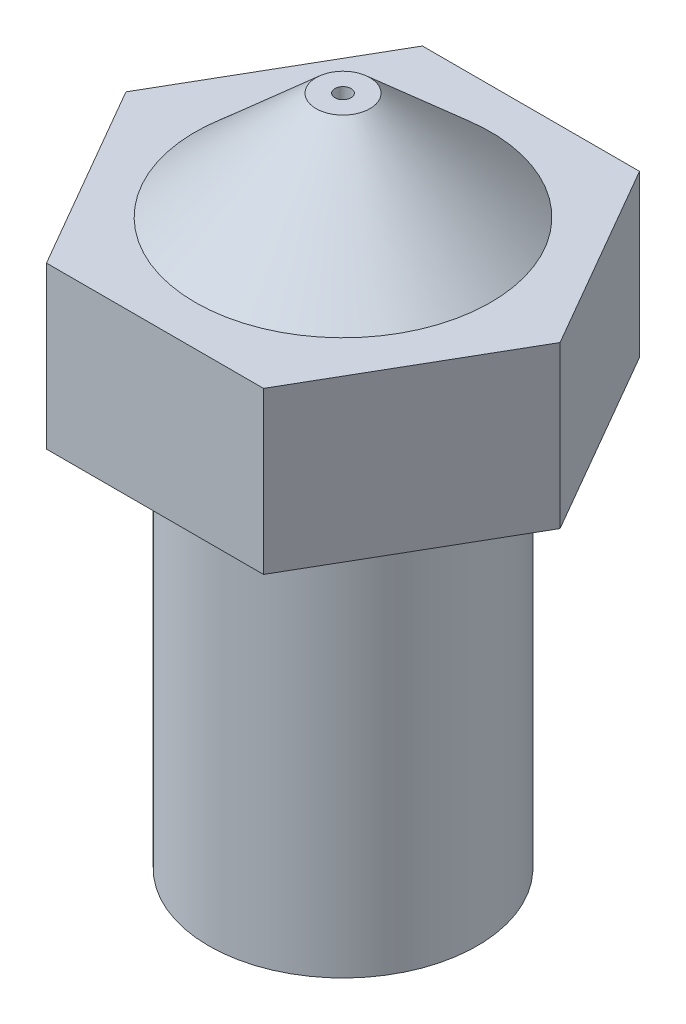
SolidWorks part; units mm, degrees
ref_plane "Front Plane" through (0, 0, 0) normal (0, 0, 1) x (1, 0, 0)
ref_plane "Top Plane" through (0, 0, 0) normal (0, 1, 0) x (1, 0, 0)
ref_plane "Right Plane" through (0, 0, 0) normal (1, 0, 0) x (0, 0, -1)
sketch "Sketch1" plane through (0, 0, 0) normal (0, 1, 0) x (1, 0, 0)
  line L1 (4.0415, 0) -> (2.0207, 3.5)
  line L2 (2.0207, 3.5) -> (-2.0207, 3.5)
  line L3 (-2.0207, 3.5) -> (-4.0415, 0)
  line L4 (-4.0415, 0) -> (-2.0207, -3.5)
  line L5 (-2.0207, -3.5) -> (2.0207, -3.5)
  line L6 (2.0207, -3.5) -> (4.0415, 0)
  circle A0 centre (0, 0) radius 3.5 construction
  dimension "D1" = 7
extrude "Boss-Extrude1" add sketch "Sketch1" along normal blind 3
sketch "Sketch2" plane through (0, 3, 0) normal (0, 1, 0) x (1, 0, 0)
  circle A0 centre (0, 0) radius 2.75
  dimension "D1" = 5.5
extrude "Boss-Extrude2" add sketch "Sketch2" along normal blind 2 draft 48.36
sketch "Sketch4" plane through (0, 5, 0) normal (0, 1, 0) x (1, 0, 0)
  circle A0 centre (0, 0) radius 0.15
  dimension "D1" = 0.3
extrude "Cut-Extrude1" cut sketch "Sketch4" against normal blind 1.5
sketch "Sketch6" plane through (0, 0, 0) normal (0, -1, 0) x (1, 0, 0)
  circle A0 centre (0, 0) radius 2.5
  dimension "D1" = 5
extrude "Boss-Extrude3" add sketch "Sketch6" along normal blind 7.5
sketch "Sketch7" plane through (0, -7.5, 0) normal (0, -1, 0) x (1, 0, 0)
  circle A0 centre (0, 0) radius 1
  dimension "D1" = 2
extrude "Cut-Extrude3" cut sketch "Sketch7" against normal up to surface (11 mm away) up to face at (0, 3.5, 0.15)
